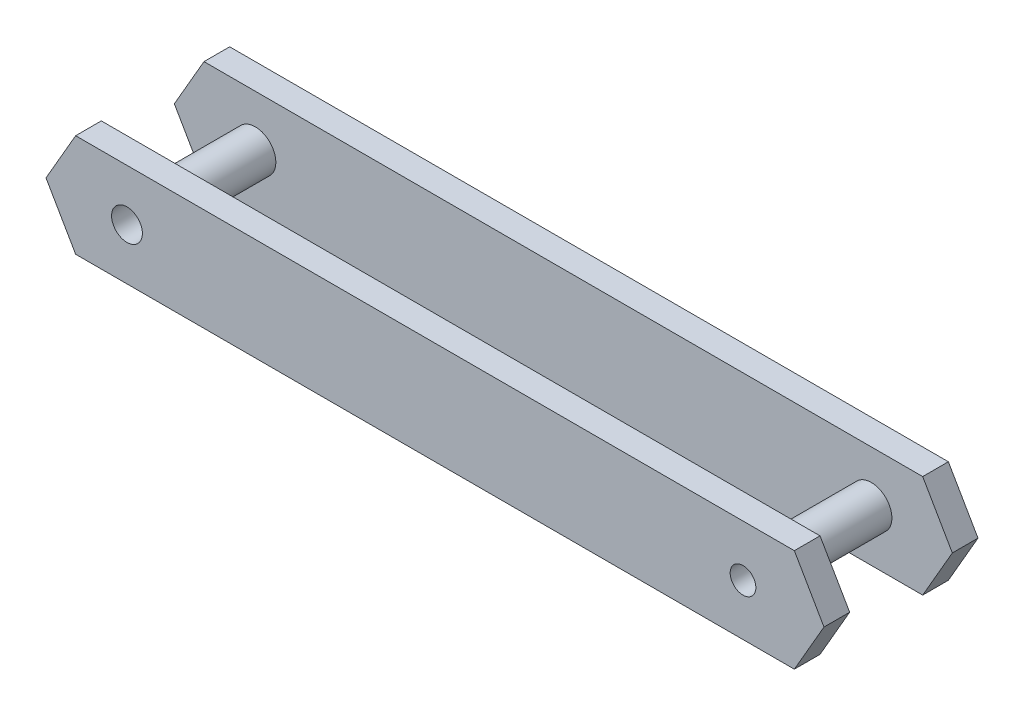
SolidWorks part; units mm, degrees
ref_plane "Front Plane" through (0, 0, 0) normal (0, 0, 1) x (1, 0, 0)
ref_plane "Top Plane" through (0, 0, 0) normal (0, 1, 0) x (1, 0, 0)
ref_plane "Right Plane" through (0, 0, 0) normal (1, 0, 0) x (0, 0, -1)
sketch "Sketch1" plane through (0, 0, 0) normal (0, 0, 1) x (1, 0, 0)
  line L0 (0, 0) -> (600, 0) construction
  circle A0 centre (0, 0) radius 20
  circle A1 centre (600, 0) radius 20
  dimension "D2" = 40
  dimension "D1" = 600
extrude "Boss-Extrude1" add sketch "Sketch1" along normal mid plane 100
sketch "Sketch2" plane through (0, 0, 50) normal (0, 0, 1) x (1, 0, 0)
  line L0 (-50, 50) -> (-78.8675, 0)
  line L1 (-50, -50) -> (650, -50)
  line L2 (-50, -50) -> (-50, 50) construction
  line L3 (-50, 50) -> (650, 50)
  line L4 (650, -50) -> (650, 50) construction
  line L5 (-78.8675, 0) -> (-50, -50)
  line L6 (650, 50) -> (678.8675, 0)
  line L7 (678.8675, 0) -> (650, -50)
  circle A2 centre (600, 0) radius 20 construction
  point P6 (-50, 0)
  dimension "D4" = 120
  dimension "D3" = 50
  dimension "D1" = 100
  dimension "D2" = 50
  dimension "D5" = 120
extrude "Boss-Extrude2" add sketch "Sketch2" along normal blind 25 separate body
mirror "Mirror1" about plane through (0, 0, 0) normal (0, 0, 1) of bodies 107
sketch "Sketch3" plane through (0, 0, 75) normal (0, 0, 1) x (1, 0, 0)
  circle A0 centre (0, 0) radius 15
  circle A1 centre (700, 0) radius 15
  dimension "D2" = 30
  dimension "D1" = 700
extrude "Cut-Extrude1" cut sketch "Sketch3" against normal through all
sketch "Sketch4" plane through (0, 0, 75) normal (0, 0, 1) x (1, 0, 0)
  circle A2 centre (600, 0) radius 12.5
  dimension "D1" = 25
extrude "Cut-Extrude2" cut sketch "Sketch4" against normal through all
